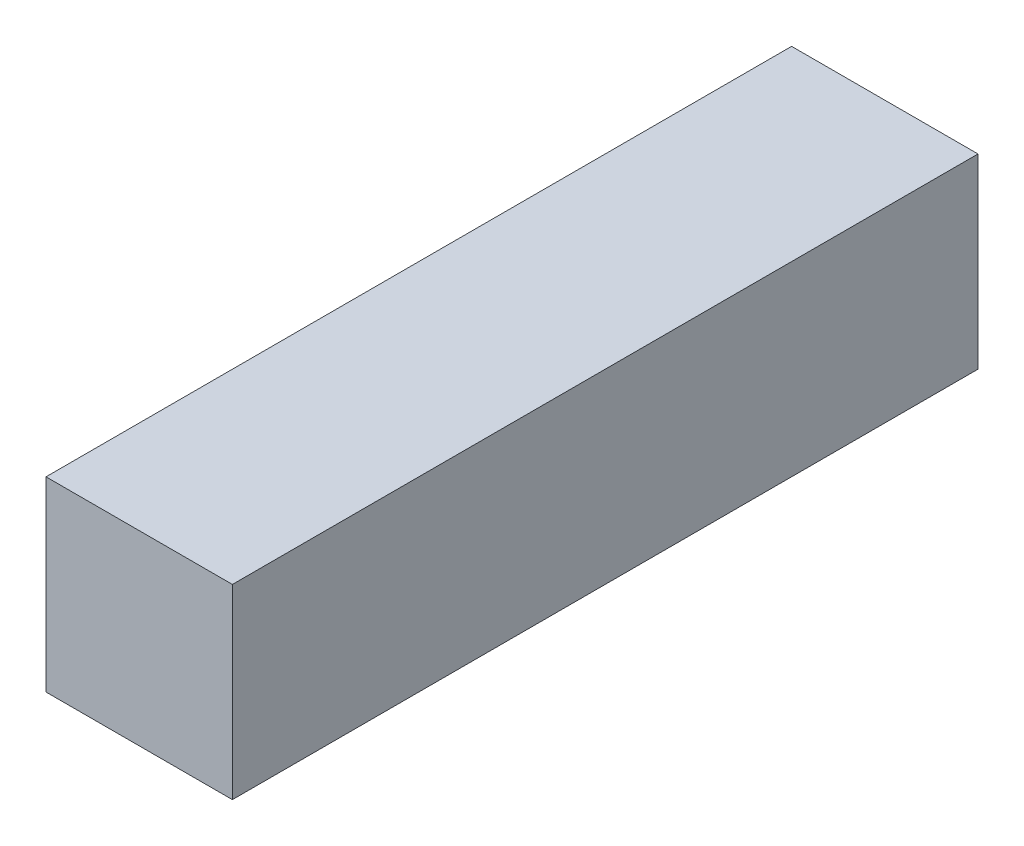
SolidWorks part; units mm, degrees
material "AISI 1020"
ref_plane "Plano frontal" through (0, 0, 0) normal (0, 0, 1) x (1, 0, 0)
ref_plane "Plano superior" through (0, 0, 0) normal (0, 1, 0) x (1, 0, 0)
ref_plane "Plano direito" through (0, 0, 0) normal (1, 0, 0) x (0, 0, -1)
sketch "Esboço1" plane through (0, 0, 0) normal (0, 0, 1) x (1, 0, 0)
  line L1 (0, 0) -> (5, 0)
  line L2 (0, 0) -> (0, 5)
  line L3 (0, 5) -> (5, 5)
  line L4 (5, 0) -> (5, 5)
  dimension "D1" = 5
extrude "Extrusão1" add sketch "Esboço1" along normal blind 20
